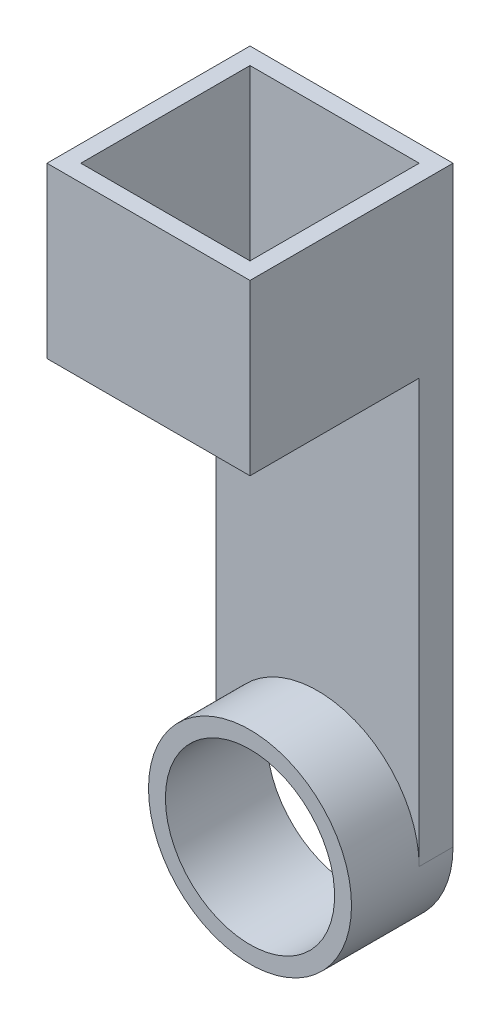
SolidWorks part; units mm, degrees
material "ABS"
ref_plane "前视基准面" through (0, 0, 0) normal (0, 0, 1) x (1, 0, 0)
ref_plane "上视基准面" through (0, 0, 0) normal (0, 1, 0) x (1, 0, 0)
ref_plane "右视基准面" through (0, 0, 0) normal (1, 0, 0) x (0, 0, -1)
other "Configuration Table"
sketch "草图1" plane through (0, 0, 0) normal (0, 0, 1) x (1, 0, 0)
  line L0 (-6, 0) -> (6, 0)
  line L1 (6, 0) -> (6, 25)
  line L2 (6, 25) -> (-6, 25)
  line L3 (-6, 25) -> (-6, 0)
  circle A0 centre (0, 0) radius 5
  circle A1 centre (0, 0) radius 6
extrude "凸台-拉伸1" add sketch "草图1" along normal blind 2 contours A1 L1 L2 L3
ref_plane "基准面1" through (6, 0, 0) normal (0, 1, 0) x (1, 0, 0)
ref_plane "基准面2" through (-6, 0, 0) normal (0, -1, 0) x (-1, 0, 0)
sketch "草图4" plane through (0, 0, 0) normal (0, 0, -1) x (-1, 0, 0)
  circle A0 centre (0, 0) radius 6
  circle A1 centre (0, 0) radius 5
extrude "凸台-拉伸2" add sketch "草图4" against normal blind 6
sketch "草图5" plane through (0, 25, 0) normal (0, 1, 0) x (1, 0, 0)
  line L1 (-6, 0) -> (6, 0)
  line L2 (-6, 0) -> (-6, -12)
  line L3 (-6, -12) -> (6, -12)
  line L4 (6, 0) -> (6, -12)
extrude "凸台-拉伸3" add sketch "草图5" along normal blind 10
sketch "草图6" plane through (0, 35, 0) normal (0, 1, 0) x (1, 0, 0)
  line L0 (-6, 0) -> (6, -12)
  line L1 (6, 0) -> (-6, 0) construction
  line L2 (-6, 0) -> (-6, -12) construction
  line L4 (-5, -11) -> (5, -11)
  line L5 (-5, -11) -> (-5, -1)
  line L6 (-5, -1) -> (5, -1)
  line L7 (5, -11) -> (5, -1)
  line L8 (-5, -11) -> (5, -1) construction
  line L9 (-5, -1) -> (5, -11) construction
  point P7 (0, -6)
extrude "切除-拉伸1" cut sketch "草图6" against normal blind 10 contours L0 L7 L6 | L5 L4 L0
